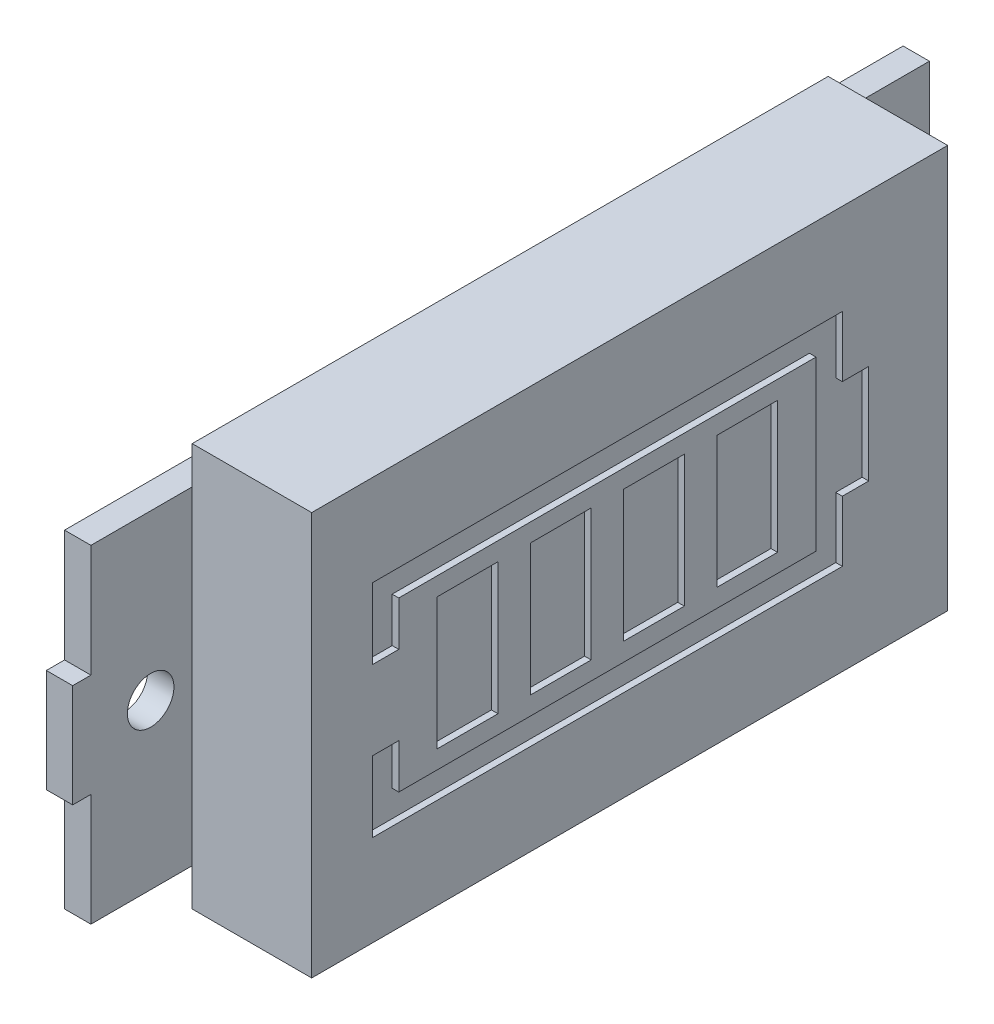
SolidWorks part; units mm, degrees
ref_plane "Alzado" through (0, 0, 0) normal (0, 0, 1) x (1, 0, 0)
ref_plane "Planta" through (0, 0, 0) normal (0, 1, 0) x (1, 0, 0)
ref_plane "Vista lateral" through (0, 0, 0) normal (1, 0, 0) x (0, 0, -1)
sketch "Croquis1" plane through (0, 0, 0) normal (1, 0, 0) x (0, 0, -1)
  line L1 (-15.7, 9.95) -> (15.7, 9.95)
  line L2 (-15.7, 9.95) -> (-15.7, -9.95)
  line L3 (-15.7, -9.95) -> (15.7, -9.95)
  line L4 (15.7, 9.95) -> (15.7, -9.95)
  line L5 (-15.7, 9.95) -> (15.7, -9.95) construction
  line L6 (-15.7, -9.95) -> (15.7, 9.95) construction
  point P0 (0, 0)
  dimension "D1" = 19.9
  dimension "D2" = 31.4
extrude "Saliente-Extruir1" add sketch "Croquis1" along normal blind 5.9
sketch "Croquis2" plane through (0, 0, 0) normal (-1, 0, 0) x (0, 0, 1)
  line L0 (21.6, 2.55) -> (21.6, -2.55)
  line L1 (-20.7, 8.1) -> (20.7, 8.1)
  line L2 (-20.7, 8.1) -> (-20.7, 2.55)
  line L3 (-20.7, -8.1) -> (20.7, -8.1)
  line L4 (20.7, 8.1) -> (20.7, 2.55)
  line L5 (-20.7, 8.1) -> (20.7, -8.1) construction
  line L6 (-20.7, -8.1) -> (20.7, 8.1) construction
  line L7 (21.6, -2.55) -> (20.7, -2.55)
  line L8 (21.6, 2.55) -> (20.7, 2.55)
  line L9 (20.7, -2.55) -> (20.7, -8.1)
  line L10 (-20.7, 2.55) -> (-21.6, 2.55)
  line L11 (-21.6, 2.55) -> (-21.6, -2.55)
  line L12 (-20.7, -2.55) -> (-21.6, -2.55)
  line L13 (-20.7, -2.55) -> (-20.7, -8.1)
  circle A0 centre (-17.75, 0) radius 1.15
  circle A1 centre (17.75, 0) radius 1.15
  point P1 (0, 0)
  point P8 (21.6, 0)
  point P13 (-21.6, 0)
  dimension "D7" = 2.3
  dimension "D1" = 41.4
  dimension "D2" = 16.2
  dimension "D3" = 5.1
  dimension "D4" = 0.9
  dimension "D5" = 5.1
  dimension "D6" = 0.9
  dimension "D8" = 3.85
  dimension "D10" = 3.85
  dimension "D9" = 2
extrude "Saliente-Extruir2" add sketch "Croquis2" along normal blind 1.3
sketch "Croquis3" plane through (-1.3, 0, 0) normal (-1, 0, 0) x (0, 0, 1)
  line L0 (-20.7, -8.1) -> (20.7, -8.1) construction
  line L1 (-12.4, 4.3) -> (-8.5, 4.3)
  line L2 (-12.4, 4.3) -> (-12.4, -4.6)
  line L3 (-12.4, -4.6) -> (-8.5, -4.6)
  line L4 (-8.5, 4.3) -> (-8.5, -4.6)
  line L5 (-12.4, 4.3) -> (-8.5, -4.6) construction
  line L6 (-12.4, -4.6) -> (-8.5, 4.3) construction
  line L7 (-21.6, 2.55) -> (-21.6, -2.55) construction
  point P0 (-10.45, -0.15)
  dimension "D1" = 8.9
  dimension "D2" = 3.5
  dimension "D3" = 3.9
  dimension "D4" = 9.2
extrude "Saliente-Extruir3" add sketch "Croquis3" along normal blind 1.3
sketch "Croquis4" plane through (-1.3, 0, 0) normal (-1, 0, 0) x (0, 0, 1)
  line L0 (-12.4, -4.6) -> (-8.5, -4.6) construction
  line L1 (-8.5, -3.75) -> (-6.5, -3.75)
  line L2 (-8.5, -3.75) -> (-8.5, -4.35)
  line L3 (-8.5, -4.35) -> (-6.5, -4.35)
  line L4 (-6.5, -3.75) -> (-6.5, -4.35)
  line L5 (-8.5, -3.75) -> (-6.5, -4.35) construction
  line L6 (-8.5, -4.35) -> (-6.5, -3.75) construction
  line L7 (-8.5, -4.6) -> (-8.5, 4.3) construction
  point P0 (-7.5, -4.05)
  dimension "D1" = 0.6
  dimension "D2" = 2
  dimension "D3" = 0.25
extrude "Saliente-Extruir4" add sketch "Croquis4" along normal blind 0.325
pattern_linear "MatrizL1" count 2 spacing 5.9 along (0, 0, -1) count 5 spacing 1.7 along (0, 1, 0) of "Saliente-Extruir4"
sketch "Croquis5" plane through (5.9, 0, 0) normal (1, 0, 0) x (0, 0, -1)
  line L0 (-12.7, 1.95) -> (-12.7, 5.45)
  line L1 (-12.7, 5.45) -> (10.5, 5.45)
  line L2 (10.5, 5.45) -> (10.5, 2.45)
  line L3 (10.5, 2.45) -> (11.8, 2.45)
  line L4 (11.8, 2.45) -> (11.8, -2.45)
  line L5 (11.8, -2.45) -> (10.5, -2.45)
  line L6 (10.5, -2.45) -> (10.5, -5.45)
  line L7 (10.5, -5.45) -> (-12.7, -5.45)
  line L8 (-12.7, -5.45) -> (-12.7, -1.95)
  line L9 (-15.7, 9.95) -> (-15.7, -9.95) construction
  line L10 (-11.4, 1.95) -> (-11.4, 4.15)
  line L11 (-11.4, 4.15) -> (9.2, 4.15)
  line L12 (9.2, 4.15) -> (9.2, 1.15)
  line L13 (9.2, -1.15) -> (9.2, 1.15)
  line L14 (-11.4, -1.95) -> (-12.7, -1.95)
  line L15 (-12.7, 1.95) -> (-11.4, 1.95)
  line L16 (9.2, -1.15) -> (9.2, -4.15)
  line L17 (9.2, -4.15) -> (-11.4, -4.15)
  line L18 (-11.4, -4.15) -> (-11.4, -1.95)
  line L19 (9.2, 1.15) -> (10.5, 1.15) construction
  line L20 (10.5, -1.15) -> (9.2, -1.15) construction
  line L21 (10.5, 1.15) -> (10.5, -1.15) construction
  line L22 (-0.3, 3.25) -> (-0.3, -3.25)
  line L23 (4.3, 3.25) -> (7.3, 3.25)
  line L24 (4.3, 3.25) -> (4.3, -3.25)
  line L25 (4.3, -3.25) -> (7.3, -3.25)
  line L26 (7.3, 3.25) -> (7.3, -3.25)
  line L27 (4.3, 3.25) -> (7.3, -3.25) construction
  line L28 (4.3, -3.25) -> (7.3, 3.25) construction
  line L29 (-0.3, 3.25) -> (2.7, 3.25)
  line L30 (2.7, 3.25) -> (2.7, -3.25)
  line L31 (-0.3, -3.25) -> (2.7, -3.25)
  line L32 (-4.9, 3.25) -> (-4.9, -3.25)
  line L33 (-4.9, 3.25) -> (-1.9, 3.25)
  line L34 (-1.9, 3.25) -> (-1.9, -3.25)
  line L35 (-4.9, -3.25) -> (-1.9, -3.25)
  line L36 (-9.5, 3.25) -> (-9.5, -3.25)
  line L37 (-9.5, 3.25) -> (-6.5, 3.25)
  line L38 (-6.5, 3.25) -> (-6.5, -3.25)
  line L39 (-9.5, -3.25) -> (-6.5, -3.25)
  point P2 (11.8, 0)
  point P14 (5.8, 0)
  dimension "D1" = 3.5
  dimension "D2" = 3.5
  dimension "D3" = 23.2
  dimension "D4" = 3
  dimension "D5" = 3
  dimension "D6" = 4.9
  dimension "D7" = 3
  dimension "D8" = 23.2
  dimension "D9" = 1.3
  dimension "D11" = 3
  dimension "D12" = 6.5
  dimension "D13" = 1.9
  dimension "D10" = 1.3
  dimension "D14" = 4
extrude "Cortar-Extruir1" cut sketch "Croquis5" against normal blind 0.325
